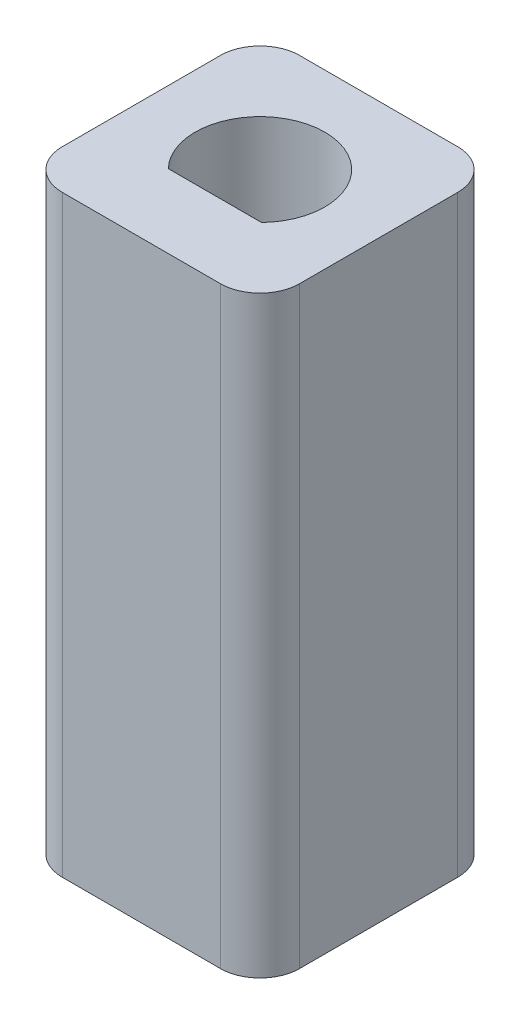
SolidWorks part; units mm, degrees
ref_plane "Front Plane" through (0, 0, 0) normal (0, 0, 1) x (1, 0, 0)
ref_plane "Top Plane" through (0, 0, 0) normal (0, 1, 0) x (1, 0, 0)
ref_plane "Right Plane" through (0, 0, 0) normal (1, 0, 0) x (0, 0, -1)
sketch "Sketch1" plane through (0, 0, 0) normal (0, -1, 0) x (1, 0, 0)
  line L0 (1.118, 1) -> (-1.118, 1) construction
  arc A0 (-1.118, 1) -> (1.118, 1) centre (0, 0) ccw construction
  point P3 (0, 0)
  dimension "D1" = 1.5
  dimension "D2" = 2.5
sketch "Sketch2" plane through (0, 0, 0) normal (0, 1, 0) x (1, 0, 0)
  line L2 (-1.179, -1.14) -> (1.179, -1.14)
  line L3 (-1.179, -1.14) -> (1.179, -1.14)
  line L4 (-3, 3) -> (3, 3)
  line L5 (-3, 3) -> (-3, -3)
  line L6 (-3, -3) -> (3, -3)
  line L7 (3, 3) -> (3, -3)
  line L8 (0, -3) -> (0, 3) construction
  line L9 (-3, 0) -> (3, 0) construction
  arc A3 (1.179, -1.14) -> (-1.179, -1.14) centre (0, 0) ccw
  arc A4 (1.179, -1.14) -> (-1.179, -1.14) centre (0, 0) ccw
  dimension "D2" = 6
  dimension "D1" = 0.14
extrude "Boss-Extrude1" add sketch "Sketch2" along normal blind 8 contours L7 L6 L5 L4
sketch "Sketch6" plane through (0, 0, 0) normal (0, 1, 0) x (1, 0, 0)
  line L0 (0.935, -1.435) -> (0.935, -2.35)
  line L1 (-0.935, 2.35) -> (0.935, 2.35) construction
  line L2 (-0.935, 2.35) -> (-0.935, 1.435)
  line L3 (-0.935, -2.35) -> (0.935, -2.35) construction
  line L4 (0.935, 2.35) -> (0.935, 1.435)
  line L5 (0, -2.35) -> (0, 0) construction
  line L6 (0, 0) -> (0, 2.35) construction
  line L7 (-2.35, 0.935) -> (-1.435, 0.935)
  line L8 (-2.35, 0.935) -> (-2.35, -0.935) construction
  line L9 (-2.35, -0.935) -> (-1.435, -0.935)
  line L10 (2.35, 0.935) -> (2.35, -0.935) construction
  line L11 (0, 0) -> (2.35, 0) construction
  line L12 (-2.35, 0) -> (0, 0) construction
  line L13 (1.435, -0.935) -> (2.35, -0.935)
  line L14 (-0.935, -1.435) -> (-0.935, -2.35)
  line L15 (1.435, 0.935) -> (2.35, 0.935)
  arc A0 (-0.935, 1.435) -> (-1.435, 0.935) centre (-1.435, 1.435) cw
  arc A1 (-1.435, -0.935) -> (-0.935, -1.435) centre (-1.435, -1.435) cw
  arc A2 (0.935, -1.435) -> (1.435, -0.935) centre (1.435, -1.435) cw
  arc A3 (0.935, 1.435) -> (1.435, 0.935) centre (1.435, 1.435) ccw
  arc A4 (2.35, -0.935) -> (2.35, 0.935) centre (0, 0) ccw
  arc A5 (0.935, 2.35) -> (-0.935, 2.35) centre (0, 0) ccw
  arc A6 (-2.35, 0.935) -> (-2.35, -0.935) centre (0, 0) ccw
  arc A7 (-0.935, -2.35) -> (0.935, -2.35) centre (0, 0) ccw
  point P0 (0, 0)
  point P4 (0, 0)
  point P10 (0, 0)
  point P22 (-0.935, -0.935)
  point P27 (0.935, -0.935)
  point P30 (0.935, 0.935)
  dimension "D3" = 0.5
  dimension "D1" = 1.87
  dimension "D2" = 2.35
sketch "Sketch7" plane through (0, 0, 0) normal (0, -1, 0) x (-1, 0, 0)
  line L1 (-3, 3) -> (3, 3)
  line L2 (-3, 3) -> (-3, -3)
  line L3 (-3, -3) -> (3, -3)
  line L4 (3, 3) -> (3, -3)
  line L5 (0, -3) -> (0, 3) construction
  line L6 (-3, 0) -> (3, 0) construction
  line L14 (-2.35, -0.935) -> (-1.435, -0.935)
  line L15 (-1.435, 0.935) -> (-2.35, 0.935)
  line L16 (-0.935, 2.35) -> (-0.935, 1.435)
  line L17 (0.935, 1.435) -> (0.935, 2.35)
  line L18 (2.35, 0.935) -> (1.435, 0.935)
  line L19 (1.435, -0.935) -> (2.35, -0.935)
  line L20 (0.935, -2.35) -> (0.935, -1.435)
  line L21 (-0.935, -1.435) -> (-0.935, -2.35)
  line L22 (-2.35, -0.935) -> (-1.435, -0.935)
  line L23 (-1.435, 0.935) -> (-2.35, 0.935)
  line L24 (-0.935, 2.35) -> (-0.935, 1.435)
  line L25 (0.935, 1.435) -> (0.935, 2.35)
  line L26 (2.35, 0.935) -> (1.435, 0.935)
  line L27 (1.435, -0.935) -> (2.35, -0.935)
  line L28 (0.935, -2.35) -> (0.935, -1.435)
  line L29 (-0.935, -1.435) -> (-0.935, -2.35)
  arc A8 (-0.935, -1.435) -> (-1.435, -0.935) centre (-1.435, -1.435) ccw
  arc A9 (-2.35, 0.935) -> (-2.35, -0.935) centre (0, 0) ccw
  arc A10 (-1.435, 0.935) -> (-0.935, 1.435) centre (-1.435, 1.435) ccw
  arc A11 (0.935, 2.35) -> (-0.935, 2.35) centre (0, 0) ccw
  arc A12 (0.935, 1.435) -> (1.435, 0.935) centre (1.435, 1.435) ccw
  arc A13 (2.35, -0.935) -> (2.35, 0.935) centre (0, 0) ccw
  arc A14 (1.435, -0.935) -> (0.935, -1.435) centre (1.435, -1.435) ccw
  arc A15 (-0.935, -2.35) -> (0.935, -2.35) centre (0, 0) ccw
  arc A16 (-0.935, -1.435) -> (-1.435, -0.935) centre (-1.435, -1.435) ccw
  arc A17 (-2.35, 0.935) -> (-2.35, -0.935) centre (0, 0) ccw
  arc A18 (-1.435, 0.935) -> (-0.935, 1.435) centre (-1.435, 1.435) ccw
  arc A19 (0.935, 2.35) -> (-0.935, 2.35) centre (0, 0) ccw
  arc A20 (0.935, 1.435) -> (1.435, 0.935) centre (1.435, 1.435) ccw
  arc A21 (2.35, -0.935) -> (2.35, 0.935) centre (0, 0) ccw
  arc A22 (1.435, -0.935) -> (0.935, -1.435) centre (1.435, -1.435) ccw
  arc A23 (-0.935, -2.35) -> (0.935, -2.35) centre (0, 0) ccw
  point P0 (0, 0)
  dimension "D1" = 6
  dimension "D2" = 0
extrude "Boss-Extrude2" add sketch "Sketch7" along normal blind 7
fillet "Fillet1" radius 1 4 edges at (3, 0.5, 3) (-3, 0.5, 3) (-3, 0.5, -3) (3, 0.5, -3)
